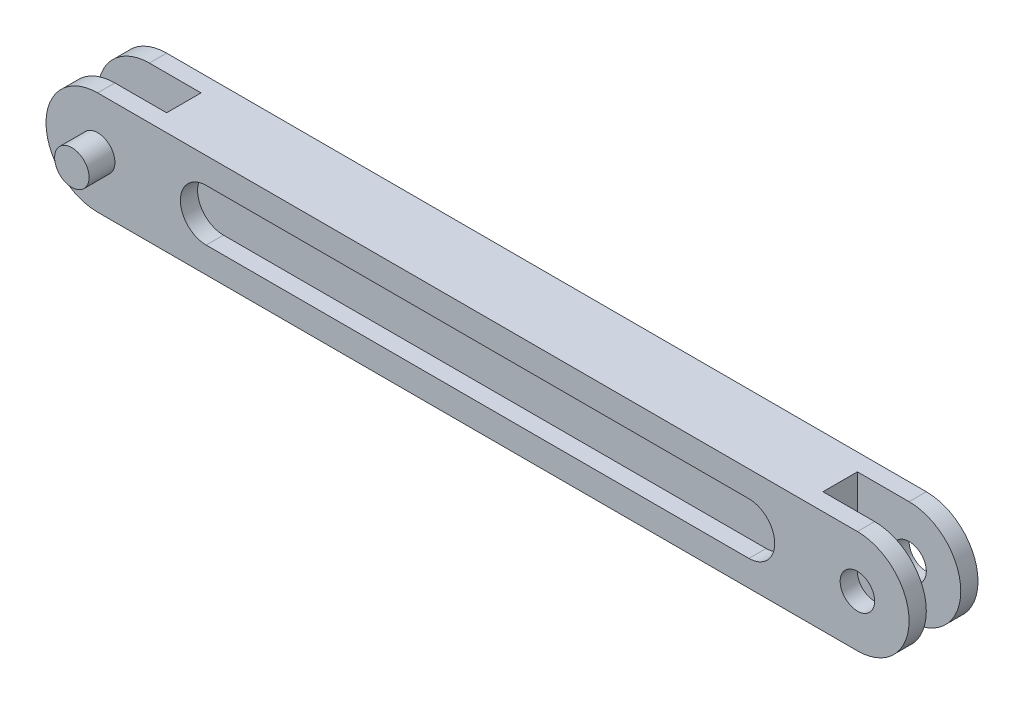
SolidWorks part; units mm, degrees
ref_plane "Front Plane" through (0, 0, 0) normal (0, 0, 1) x (1, 0, 0)
ref_plane "Top Plane" through (0, 0, 0) normal (0, 1, 0) x (1, 0, 0)
ref_plane "Right Plane" through (0, 0, 0) normal (1, 0, 0) x (0, 0, -1)
sketch "Sketch1" plane through (0, 0, 0) normal (0, 0, 1) x (1, 0, 0)
  line L0 (0, 0) -> (280, 0) construction
  line L1 (0, 19.05) -> (280, 19.05)
  line L2 (0, -19.05) -> (280, -19.05)
  arc A0 (0, 19.05) -> (0, -19.05) centre (0, 0) ccw
  arc A1 (280, -19.05) -> (280, 19.05) centre (280, 0) ccw
  circle A2 centre (0, 0) radius 6.35
  circle A3 centre (280, 0) radius 6.35
  point P3 (140, 0)
  dimension "D3" = 12.7
  dimension "D1" = 280
  dimension "D2" = 38.1
extrude "Boss-Extrude1" add sketch "Sketch1" along normal blind 25.4
sketch "Sketch2" plane through (0, 0, 25.4) normal (0, 0, 1) x (1, 0, 0)
  line L0 (40, 0) -> (240, 0) construction
  line L1 (40, 9.525) -> (240, 9.525)
  line L2 (40, -9.525) -> (240, -9.525)
  line L3 (0, 19.05) -> (280, 19.05)
  line L4 (0, 19.05) -> (280, 19.05) construction
  line L5 (280, -19.05) -> (0, -19.05)
  line L6 (280, -19.05) -> (0, -19.05) construction
  arc A0 (40, 9.525) -> (40, -9.525) centre (40, 0) ccw
  arc A1 (240, -9.525) -> (240, 9.525) centre (240, 0) ccw
  arc A2 (280, -19.05) -> (280, 19.05) centre (280, 0) ccw
  arc A3 (280, -19.05) -> (280, 19.05) centre (280, 0) ccw construction
  arc A4 (0, 19.05) -> (0, -19.05) centre (0, 0) ccw
  arc A5 (0, 19.05) -> (0, -19.05) centre (0, 0) ccw construction
  point P3 (140, 0)
  point P15 (140, 19.05)
  dimension "D1" = 200
  dimension "D2" = 19.05
extrude "Cut-Extrude1" cut sketch "Sketch2" against normal blind 6.35
ref_plane "Plane1" through (0, 0, 12.7) normal (0, 0, 1) x (1, 0, 0)
mirror "Mirror1" about plane through (0, 0, 12.7) normal (0, 0, 1) of "Cut-Extrude1"
ref_plane "Plane2" through (-19.05, 0, 0) normal (-1, 0, 0) x (0, 0, 1)
sketch "Sketch3" plane through (-19.05, 0, 0) normal (-1, 0, 0) x (0, 0, 1)
  line L0 (0, -19.05) -> (0, 19.05)
  line L1 (0, -19.05) -> (0, 19.05) construction
  line L2 (0, 19.05) -> (25.4, 19.05)
  line L3 (0, 19.05) -> (25.4, 19.05) construction
  line L4 (25.4, 19.05) -> (25.4, -19.05)
  line L5 (25.4, 19.05) -> (25.4, -19.05) construction
  line L6 (25.4, -19.05) -> (0, -19.05)
  line L7 (25.4, -19.05) -> (0, -19.05) construction
  line L8 (6.35, -19.05) -> (6.35, 19.05)
  line L9 (6.35, -19.05) -> (19.05, -19.05)
  line L10 (6.35, 19.05) -> (19.05, 19.05)
  line L11 (19.05, -19.05) -> (19.05, 19.05)
  line L12 (6.35, -19.05) -> (19.05, 19.05) construction
  line L13 (6.35, 19.05) -> (19.05, -19.05) construction
  line L14 (12.7, 19.05) -> (12.7, -19.05) construction
  point P4 (12.7, 0)
  point P5 (12.7, 0)
  dimension "D1" = 12.7
extrude "Cut-Extrude2" cut sketch "Sketch3" against normal blind 38.1
ref_plane "Plane3" through (140, 0, 0) normal (-1, 0, 0) x (0, 0, 1)
mirror "Mirror2" about plane through (140, 0, 0) normal (-1, 0, 0) of "Cut-Extrude2"
sketch "Sketch5" plane through (0, 0, 25.4) normal (0, 0, 1) x (1, 0, 0)
  circle A0 centre (0, 0) radius 6.35
  dimension "D1" = 12.7
extrude "Boss-Extrude3" add sketch "Sketch5" along normal blind 9.525 and the other way blind 34.925
